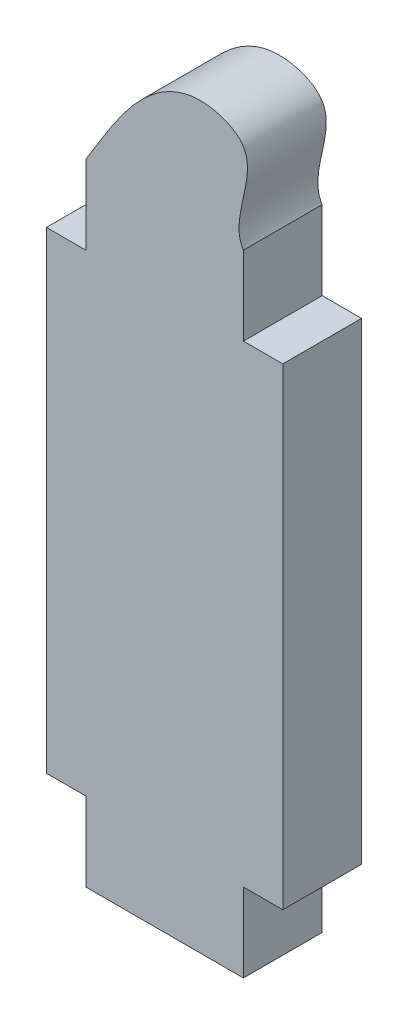
SolidWorks part; units mm, degrees
ref_plane "Front Plane" through (0, 0, 0) normal (0, 0, 1) x (1, 0, 0)
ref_plane "Top Plane" through (0, 0, 0) normal (0, 1, 0) x (1, 0, 0)
ref_plane "Right Plane" through (0, 0, 0) normal (1, 0, 0) x (0, 0, -1)
sketch "Sketch1" plane through (0, 0, 0) normal (0, 0, 1) x (1, 0, 0)
  line L1 (4.7625, -9.525) -> (-4.7625, -9.525)
  line L2 (4.7625, -9.525) -> (4.7625, 9.525)
  line L3 (4.7625, 9.525) -> (-4.7625, 9.525)
  line L4 (-4.7625, -9.525) -> (-4.7625, 9.525)
  line L5 (4.7625, -9.525) -> (-4.7625, 9.525) construction
  line L6 (4.7625, 9.525) -> (-4.7625, -9.525) construction
  line L7 (-3.175, 9.525) -> (3.175, 9.525)
  line L8 (-3.175, 9.525) -> (-3.175, 12.7)
  line L9 (-3.175, 12.7) -> (3.175, 12.7)
  line L10 (3.175, 9.525) -> (3.175, 12.7)
  line L11 (-3.175, -9.525) -> (3.175, -9.525)
  line L12 (-3.175, -9.525) -> (-3.175, -12.7)
  line L13 (-3.175, -12.7) -> (3.175, -12.7)
  line L14 (3.175, -9.525) -> (3.175, -12.7)
  spline S0 degree 3 poles (-3.175, 12.7) (-2.2138, 14.1736) (-0.3859, 17.9717) (4.3151, 16.2397) (2.5765, 13.6162) (3.175, 12.7) knots 0 0 0 0 0.552545 0.698481 1 1 1 1
  point P0 (0, 0)
  dimension "D1" = 19.05
  dimension "D2" = 9.525
  dimension "D3" = 6.35
  dimension "D4" = 1.5875
  dimension "D5" = 1.5875
  dimension "D6" = 3.175
  dimension "D7" = 3.175
  dimension "D8" = 6.35
extrude "Boss-Extrude1" add sketch "Sketch1" along normal blind 3.175 contours L4 L1 L2 L3 | L3 L10 L9 L8 | S0 L9 | L14 L1 L12 L13
